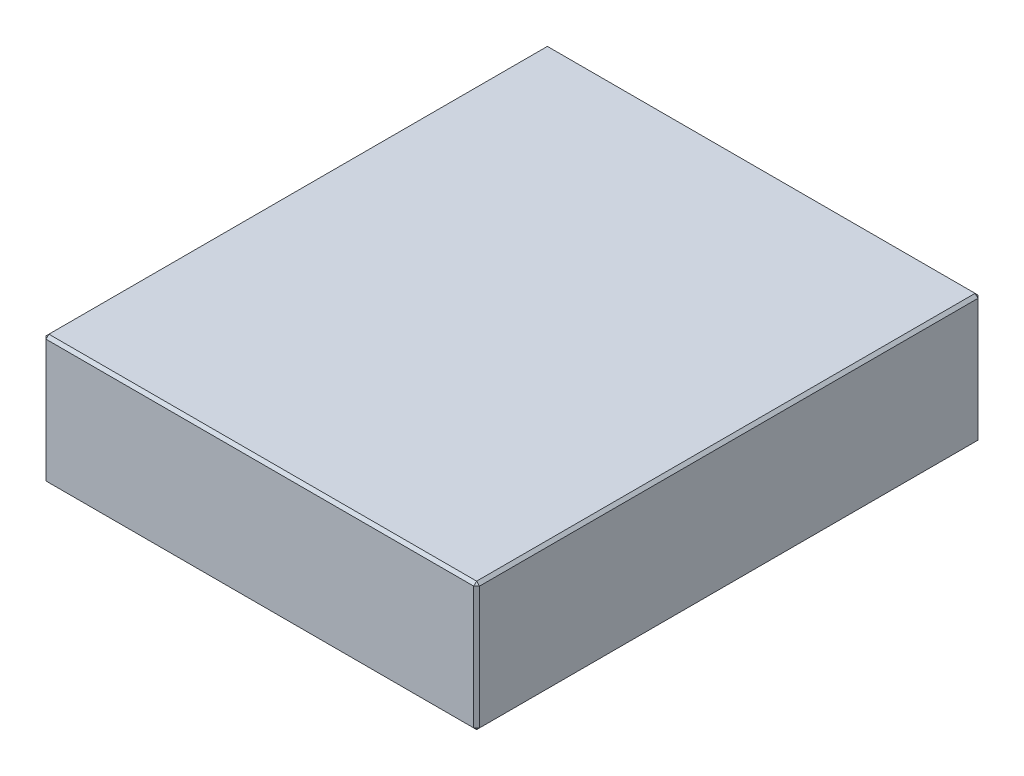
SolidWorks part; units mm, degrees
ref_plane "Přední rovina" through (0, 0, 0) normal (0, 0, 1) x (1, 0, 0)
ref_plane "Horní rovina" through (0, 0, 0) normal (0, 1, 0) x (1, 0, 0)
ref_plane "Pravá rovina" through (0, 0, 0) normal (1, 0, 0) x (0, 0, -1)
sketch "Skica1" plane through (0, 0, 0) normal (0, 0, 1) x (1, 0, 0)
  line L1 (-15, -4.45) -> (15, -4.45)
  line L2 (-15, -4.45) -> (-15, 4.45)
  line L3 (-15, 4.45) -> (15, 4.45)
  line L4 (15, -4.45) -> (15, 4.45)
  line L5 (-15, -4.45) -> (15, 4.45) construction
  line L6 (-15, 4.45) -> (15, -4.45) construction
  point P0 (0, 0)
  dimension "D1" = 30
  dimension "D2" = 8.9
extrude "Přidat vysunutím1" add sketch "Skica1" along normal blind 34.896
chamfer "Zkosení1" distance 0.2 angle 45 12 edges at (-15, 0, 0) (0, 4.45, 0) (15, 0, 0) (0, -4.45, 0) (-15, 0, 34.896) (0, 4.45, 34.896) (15, 0, 34.896) (0, -4.45, 34.896) (-15, -4.45, 17.448) (-15, 4.45, 17.448) (15, 4.45, 17.448) (15, -4.45, 17.448)
